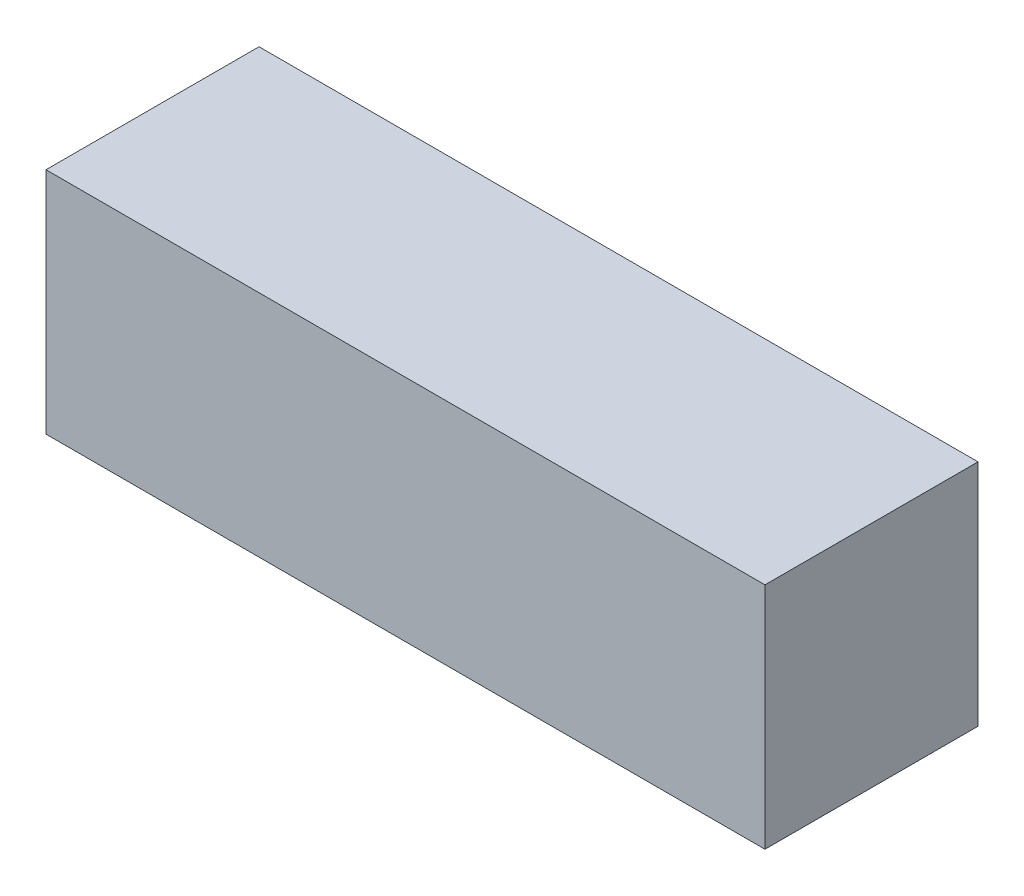
SolidWorks part; units mm, degrees
ref_plane "Front Plane" through (0, 0, 0) normal (0, 0, 1) x (1, 0, 0)
ref_plane "Top Plane" through (0, 0, 0) normal (0, 1, 0) x (1, 0, 0)
ref_plane "Right Plane" through (0, 0, 0) normal (1, 0, 0) x (0, 0, -1)
sketch "Sketch1" plane through (0, 0, 0) normal (0, 1, 0) x (1, 0, 0)
  line L1 (-67.5, -20) -> (67.5, -20)
  line L2 (-67.5, -20) -> (-67.5, 20)
  line L3 (-67.5, 20) -> (67.5, 20)
  line L4 (67.5, -20) -> (67.5, 20)
  line L5 (-67.5, -20) -> (67.5, 20) construction
  line L6 (-67.5, 20) -> (67.5, -20) construction
  point P0 (0, 0)
  dimension "D1" = 135
  dimension "D2" = 40
extrude "Boss-Extrude1" add sketch "Sketch1" along normal blind 43
